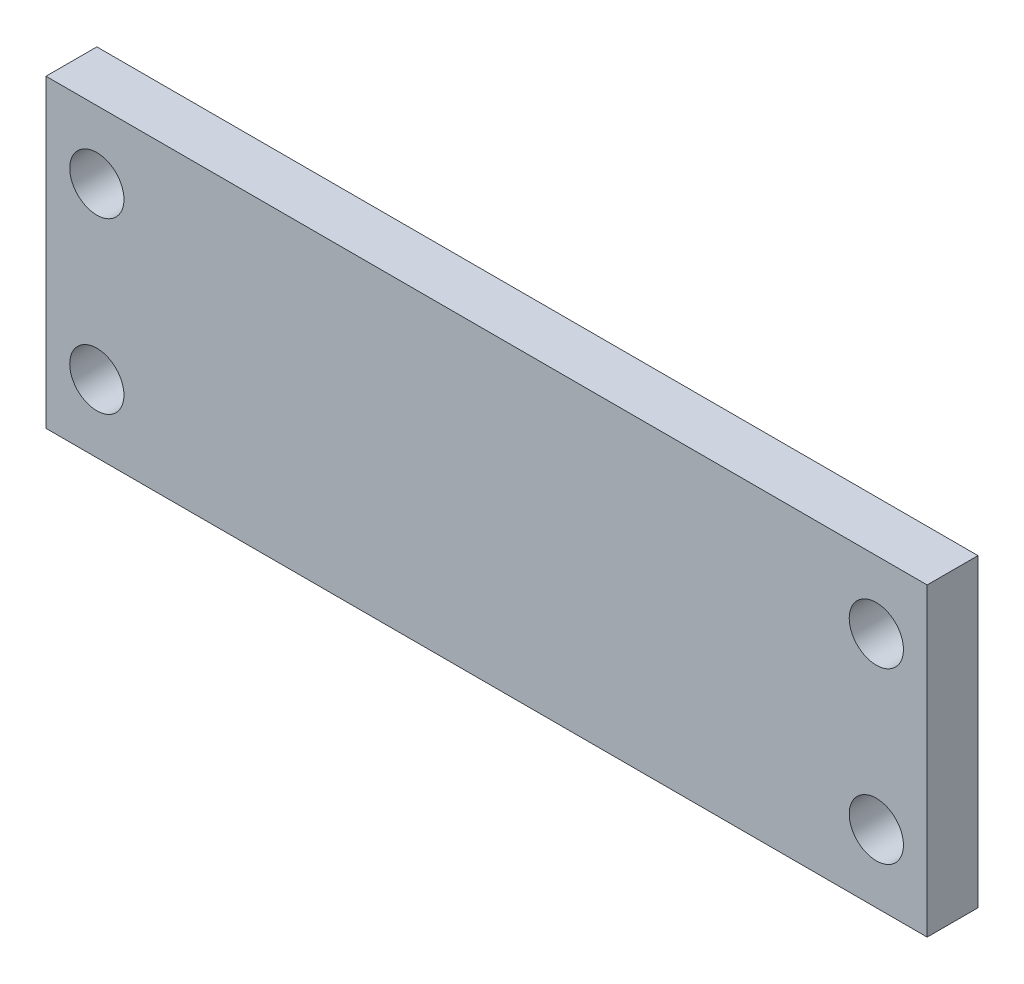
SolidWorks part; units mm, degrees
material "AISI 1020"
ref_plane "Front Plane" through (0, 0, 0) normal (0, 0, 1) x (1, 0, 0)
ref_plane "Top Plane" through (0, 0, 0) normal (0, 1, 0) x (1, 0, 0)
ref_plane "Right Plane" through (0, 0, 0) normal (1, 0, 0) x (0, 0, -1)
sketch "Sketch2" plane through (0, 0, 0) normal (0, 0, 1) x (1, 0, 0)
  line L1 (-26, -9) -> (26, -9)
  line L2 (-26, -9) -> (-26, 9)
  line L3 (-26, 9) -> (26, 9)
  line L4 (26, -9) -> (26, 9)
  circle A3 centre (-23, -5) radius 1.6
  circle A5 centre (-23, 5) radius 1.6
  circle A6 centre (23, -5) radius 1.6
  circle A7 centre (23, 5) radius 1.6
  point P0 (0, 0)
  point P5 (0, 0)
  point P20 (-21.8245, -5.2351)
  dimension "D3" = 10
  dimension "D5" = 3.2
  dimension "D6" = 3.2
  dimension "D7" = 3.2
  dimension "D8" = 3.2
  dimension "D1" = 46
  dimension "D2" = 18
  dimension "D4" = 52
extrude "Boss-Extrude1" add sketch "Sketch2" along normal blind 3
equation "\"A\"= 100"
equation "\"B\"= 100"
equation "\"C\"= 100"
equation "\"D\"= 100"
equation "\"E\"= 100"
